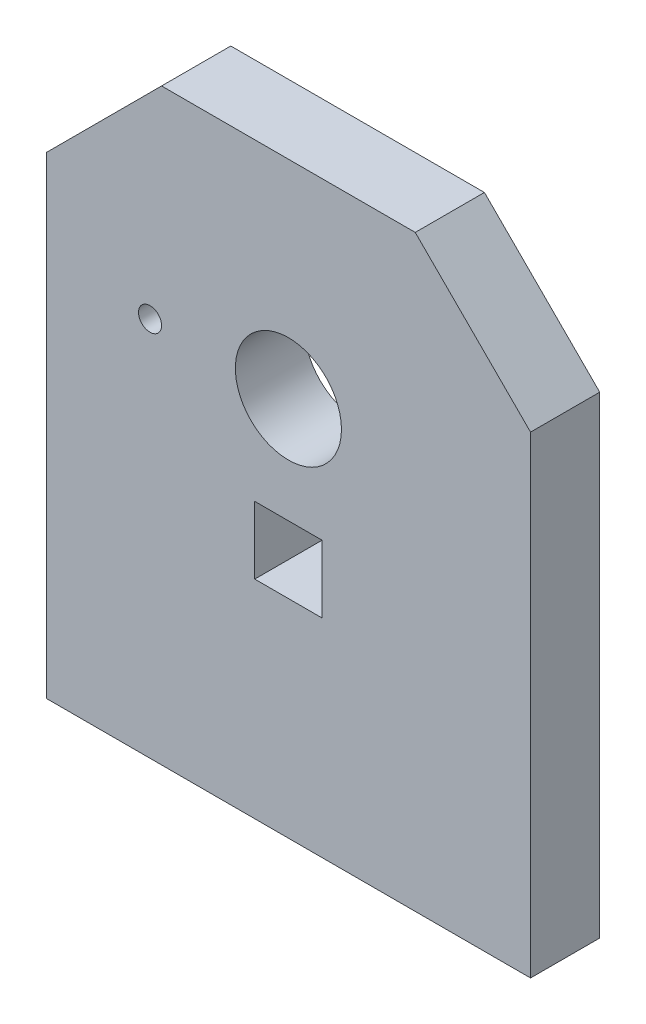
SolidWorks part; units mm, degrees
ref_plane "Front Plane" through (0, 0, 0) normal (0, 0, 1) x (1, 0, 0)
ref_plane "Top Plane" through (0, 0, 0) normal (0, 1, 0) x (1, 0, 0)
ref_plane "Right Plane" through (0, 0, 0) normal (1, 0, 0) x (0, 0, -1)
sketch "Sketch1" plane through (0, 0, 0) normal (0, 0, 1) x (1, 0, 0)
  line L0 (8.5483, 11.7097) -> (13.5483, 6.7097)
  line L1 (-7.4517, 11.7097) -> (13.5483, 11.7097)
  line L2 (-7.4517, 11.7097) -> (-7.4517, -13.7903)
  line L3 (-7.4517, -13.7903) -> (13.5483, -13.7903)
  line L4 (13.5483, 11.7097) -> (13.5483, -13.7903)
  line L5 (3.0483, 11.7097) -> (3.0483, 6.905) construction
  line L6 (-2.4517, 11.7097) -> (-7.4517, 6.7097)
  line L8 (1.5883, -1.8703) -> (4.5083, -1.8703)
  line L9 (1.5883, -1.8703) -> (1.5883, -4.7903)
  line L10 (1.5883, -4.7903) -> (4.5083, -4.7903)
  line L11 (4.5083, -1.8703) -> (4.5083, -4.7903)
  circle A0 centre (3.0483, 2.7097) radius 2.3
  circle A1 centre (-2.9517, 2.7097) radius 0.5
  point P16 (3.0483, -1.8703)
  dimension "D5" = 4.6
  dimension "D6" = 16.5
  dimension "D11" = 1
  dimension "D12" = 6
  dimension "D1" = 25.5
  dimension "D2" = 21
  dimension "D3" = 5
  dimension "D4" = 5
  dimension "D7" = 2.92
  dimension "D8" = 2.92
  dimension "D9" = 9
  dimension "D10" = 10.5
extrude "Boss-Extrude1" add sketch "Sketch1" along normal blind 3
